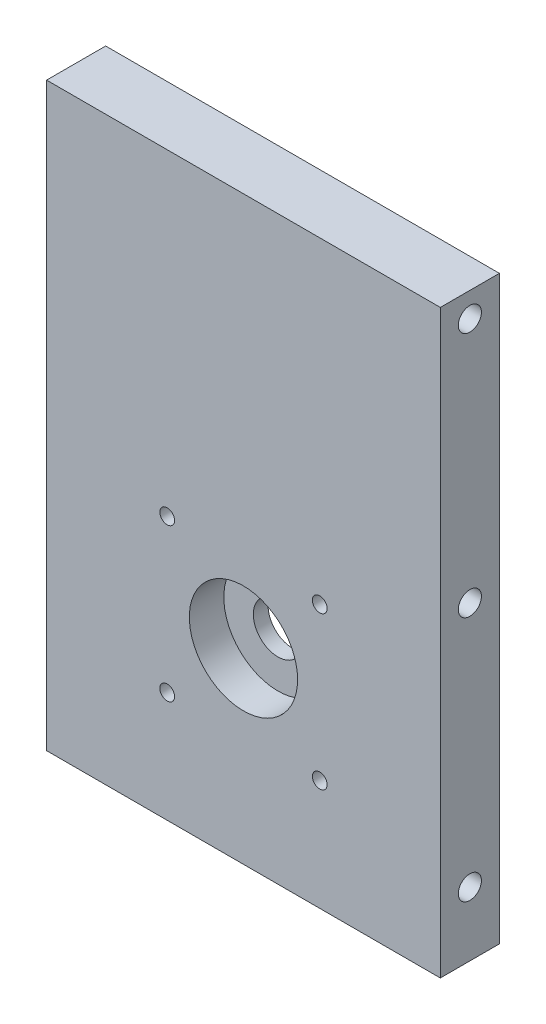
SolidWorks part; units mm, degrees
material "PLA"
ref_plane "Alzado" through (0, 0, 0) normal (0, 0, 1) x (1, 0, 0)
ref_plane "Planta" through (0, 0, 0) normal (0, 1, 0) x (1, 0, 0)
ref_plane "Vista lateral" through (0, 0, 0) normal (1, 0, 0) x (0, 0, -1)
sketch "Croquis1" plane through (0, 0, 0) normal (0, 0, 1) x (1, 0, 0)
  line L1 (0, 0) -> (80, 0)
  line L2 (0, 0) -> (0, 110)
  line L3 (0, 110) -> (80, 110)
  line L4 (80, 0) -> (80, 110)
  circle A0 centre (40, 30) radius 5
  circle A1 centre (55.5, 45.5) radius 1.5
  circle A2 centre (24.5, 45.5) radius 1.5
  circle A3 centre (24.5, 14.5) radius 1.5
  circle A4 centre (55.5, 14.5) radius 1.5
  dimension "D5" = 10
  dimension "D8" = 3
  dimension "D1" = 80
  dimension "D2" = 110
  dimension "D3" = 40
  dimension "D4" = 80
  dimension "D6" = 15.5
  dimension "D7" = 15.5
  dimension "D9" = 2
  dimension "D10" = 2
extrude "Saliente-Extruir1" add sketch "Croquis1" along normal blind 12
sketch "Croquis4" plane through (0, 0, 0) normal (0, 0, -1) x (-1, 0, 0)
  circle A0 centre (-40, 30) radius 11.25
  dimension "D1" = 22.5
extrude "Cortar-Extruir2" cut sketch "Croquis4" against normal blind 2
sketch "Croquis5" plane through (80, 0, 0) normal (1, 0, 0) x (0, 0, -1)
  line L0 (-12, 110) -> (0, 110) construction
  line L2 (-12, 0) -> (-12, 110) construction
  circle A0 centre (-6, 105) radius 2.35
  circle A1 centre (-6, 55) radius 2.35
  circle A2 centre (-6, 5) radius 2.35
  dimension "D1" = 4.7
  dimension "D2" = 5
  dimension "D3" = 6
  dimension "D4" = 3
extrude "Cortar-Extruir3" cut sketch "Croquis5" against normal blind 5
sketch "Croquis6" plane through (0, 0, 0) normal (-1, 0, 0) x (0, 0, 1)
  circle A0 centre (6, 105) radius 2.35
  circle A1 centre (6, 55) radius 2.35
  circle A2 centre (6, 5) radius 2.35
  dimension "D3" = 4.7
extrude "Cortar-Extruir4" cut sketch "Croquis6" against normal blind 5
sketch "Croquis7" plane through (0, 0, 12) normal (0, 0, 1) x (1, 0, 0)
  circle A0 centre (40, 30) radius 11
  dimension "D1" = 22
extrude "Cortar-Extruir5" cut sketch "Croquis7" against normal blind 7
sketch "Croquis8" plane through (0, 0, 12) normal (0, 0, 1) x (1, 0, 0)
  line L0 (0, 0) -> (80, 0)
  line L1 (80, 0) -> (80, -8)
  line L2 (80, -8) -> (0, -8)
  line L3 (0, -8) -> (0, 0)
  dimension "D1" = 8
extrude "Saliente-Extruir2" add sketch "Croquis8" against normal blind 12
